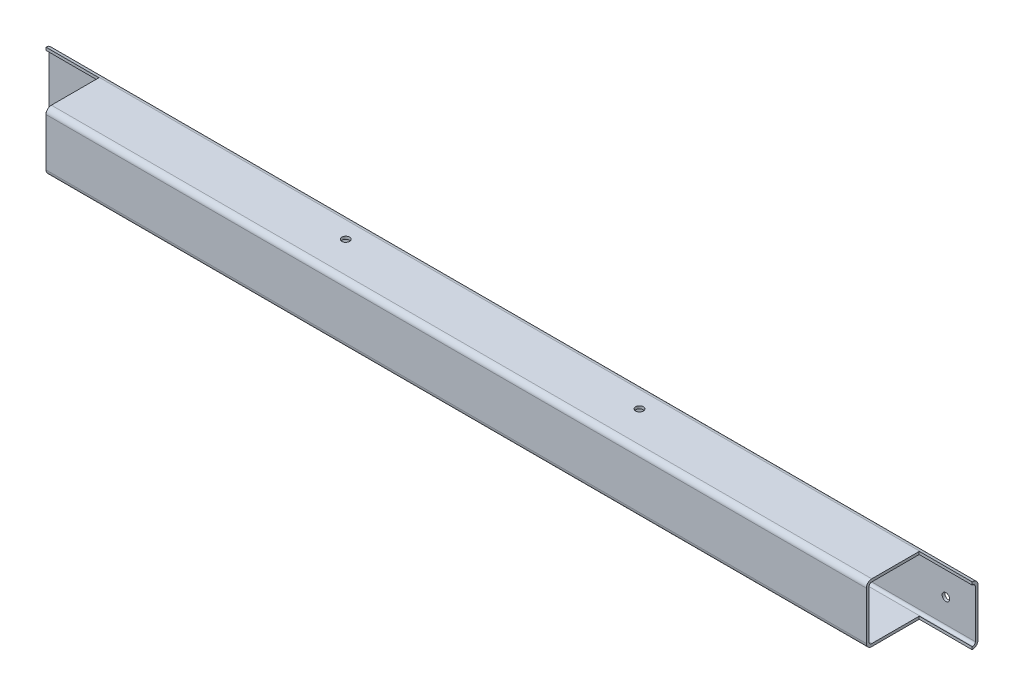
SolidWorks part; units mm, degrees
ref_plane "Front Plane" through (0, 0, 0) normal (0, 0, 1) x (1, 0, 0)
ref_plane "Top Plane" through (0, 0, 0) normal (0, 1, 0) x (1, 0, 0)
ref_plane "Right Plane" through (0, 0, 0) normal (1, 0, 0) x (0, 0, -1)
sketch "Sketch1" plane through (0, 0, 0) normal (0, 0, 1) x (1, 0, 0)
  line L0 (-394, 0) -> (394, 0)
  point P4 (0, 0)
  dimension "D1" = 788
other "Shs c450 as 50X50X2.3 SHS C450(1)"
ref_plane "Plane1" through (-394, 0, 0) normal (1, 0, 0) x (0, 1, 0)
sketch "Sketch19" plane through (-394, 0, 0) normal (1, 0, 0) x (0, 1, 0)
  line L0 (-20.4, 22.7) -> (20.4, 22.7)
  line L1 (-20.4, -25) -> (20.4, -25)
  line L2 (-25, -20.4) -> (-25, 20.4)
  line L3 (-20.4, 25) -> (20.4, 25)
  line L4 (25, -20.4) -> (25, 20.4)
  line L5 (-25, -25) -> (25, 25) construction
  line L6 (-25, 25) -> (25, -25) construction
  line L7 (22.7, -20.4) -> (22.7, 20.4)
  line L8 (-20.4, -22.7) -> (20.4, -22.7)
  line L9 (-22.7, -20.4) -> (-22.7, 20.4)
  arc A0 (-25, 20.4) -> (-20.4, 25) centre (-20.4, 20.4) cw
  arc A1 (20.4, 25) -> (25, 20.4) centre (20.4, 20.4) cw
  arc A2 (-20.4, -25) -> (-25, -20.4) centre (-20.4, -20.4) cw
  arc A3 (20.4, -25) -> (25, -20.4) centre (20.4, -20.4) ccw
  arc A4 (-22.7, 20.4) -> (-20.4, 22.7) centre (-20.4, 20.4) cw
  arc A5 (20.4, 22.7) -> (22.7, 20.4) centre (20.4, 20.4) cw
  arc A6 (20.4, -22.7) -> (22.7, -20.4) centre (20.4, -20.4) ccw
  arc A7 (-20.4, -22.7) -> (-22.7, -20.4) centre (-20.4, -20.4) cw
  point P0 (0, 0)
  point P30 (-25, 0)
  point P31 (0, 25)
  point P32 (25, 0)
  point P33 (0, -25)
  point P34 (0, 0)
  dimension "D2" = 4.6
  dimension "Thickness" = 2.3
  dimension "Width" = 50
sketch "Sketch20" plane through (0, 0, 0) normal (0, 1, 0) x (1, 0, 0)
  line L9 (-394, -25) -> (-349, -25)
  line L10 (-394, -25) -> (-394, 20)
  line L11 (-394, 20) -> (-349, 20)
  line L12 (-349, -25) -> (-349, 20)
  line L13 (394, -25) -> (349, -25)
  line L14 (394, -25) -> (394, 20)
  line L15 (394, 20) -> (349, 20)
  line L16 (349, -25) -> (349, 20)
  dimension "D1" = 45
extrude "Cut-Extrude1" cut sketch "Sketch20" against normal through all both and the other way through all
sketch "Sketch21" plane through (0, 0, -25) normal (0, 0, -1) x (-1, 0, 0)
  line L0 (-369, 0) -> (369, 0) construction
  circle A0 centre (-369, 0) radius 3.25
  circle A1 centre (369, 0) radius 3.25
  point P4 (0, 0)
  dimension "D2" = 6.5
  dimension "D1" = 738
extrude "Cut-Extrude2" cut sketch "Sketch21" against normal blind 10
sketch "Sketch22" plane through (0, 25, 0) normal (0, 1, 0) x (1, 0, 0)
  line L0 (-125, 6) -> (125, 6) construction
  line L1 (0, 0) -> (0, 6) construction
  line L2 (349, -25) -> (-349, -25) construction
  circle A0 centre (-125, 6) radius 3.25
  circle A1 centre (125, 6) radius 3.25
  point P3 (0, 6)
  dimension "D2" = 6.5
  dimension "D3" = 31
  dimension "D1" = 250
extrude "Cut-Extrude3" cut sketch "Sketch22" against normal blind 10
sketch "Sketch23" plane through (0, -25, 0) normal (0, -1, 0) x (1, 0, 0)
  circle A0 centre (-125, -6) radius 7.5
  circle A1 centre (125, -6) radius 7.5
  dimension "D1" = 15
extrude "Cut-Extrude4" cut sketch "Sketch23" against normal blind 10
